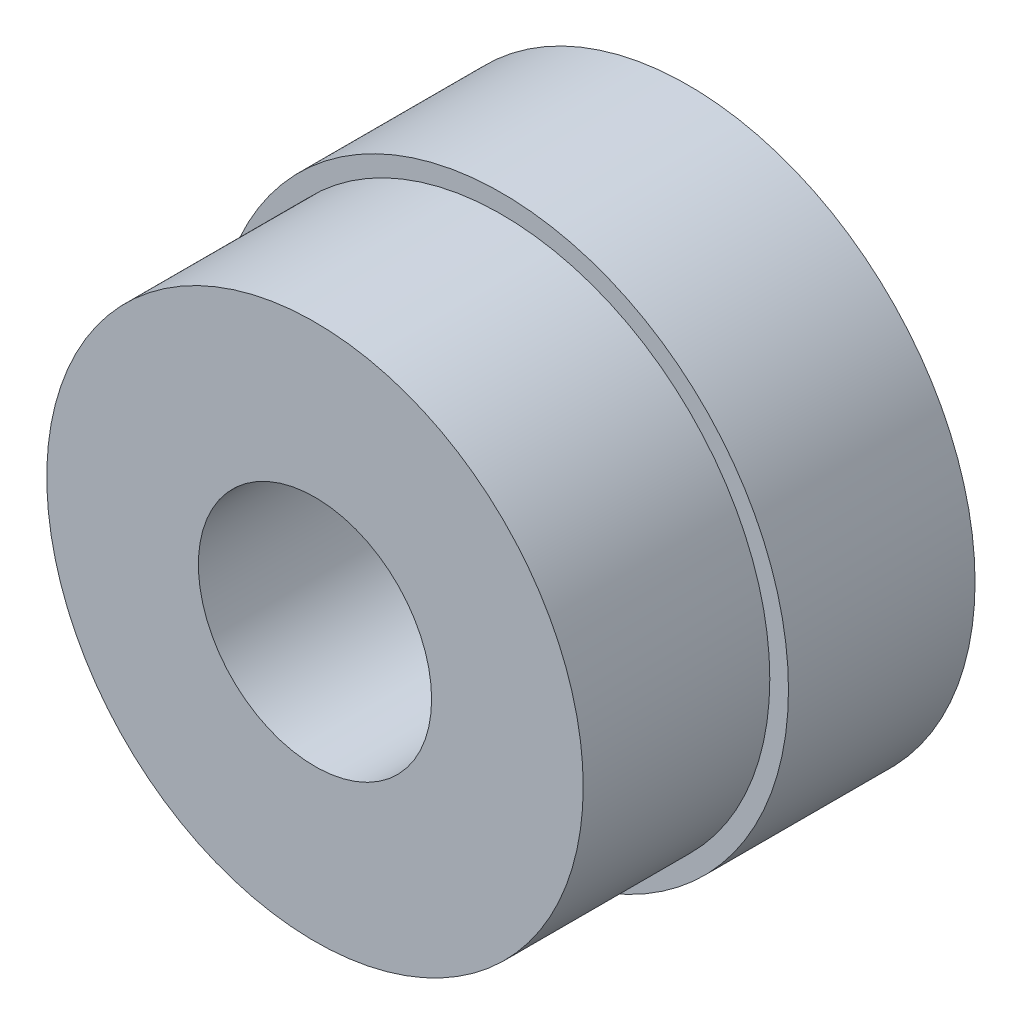
SolidWorks part; units mm, degrees
material "AISI 304"
ref_plane "Front" through (0, 0, 0) normal (0, 0, 1) x (1, 0, 0)
ref_plane "Top" through (0, 0, 0) normal (0, 1, 0) x (1, 0, 0)
ref_plane "Right" through (0, 0, 0) normal (1, 0, 0) x (0, 0, -1)
sketch "Sketch1" plane through (0, 0, 0) normal (0, 0, 1) x (1, 0, 0)
  circle A0 centre (0, 0) radius 6.15
  dimension "D1" = 12.3
extrude "Boss-Extrude1" add sketch "Sketch1" along normal blind 4
sketch "Sketch4" plane through (0, 0, 4) normal (0, 0, 1) x (1, 0, 0)
  circle A0 centre (0, 0) radius 5.75
  dimension "D1" = 11.5
extrude "Boss-Extrude3" add sketch "Sketch4" along normal blind 4
sketch "Sketch5" plane through (0, 0, 8) normal (0, 0, 1) x (1, 0, 0)
  circle A0 centre (0, 0) radius 2.5
  dimension "D1" = 5
extrude "Cut-Extrude1" cut sketch "Sketch5" against normal through all
